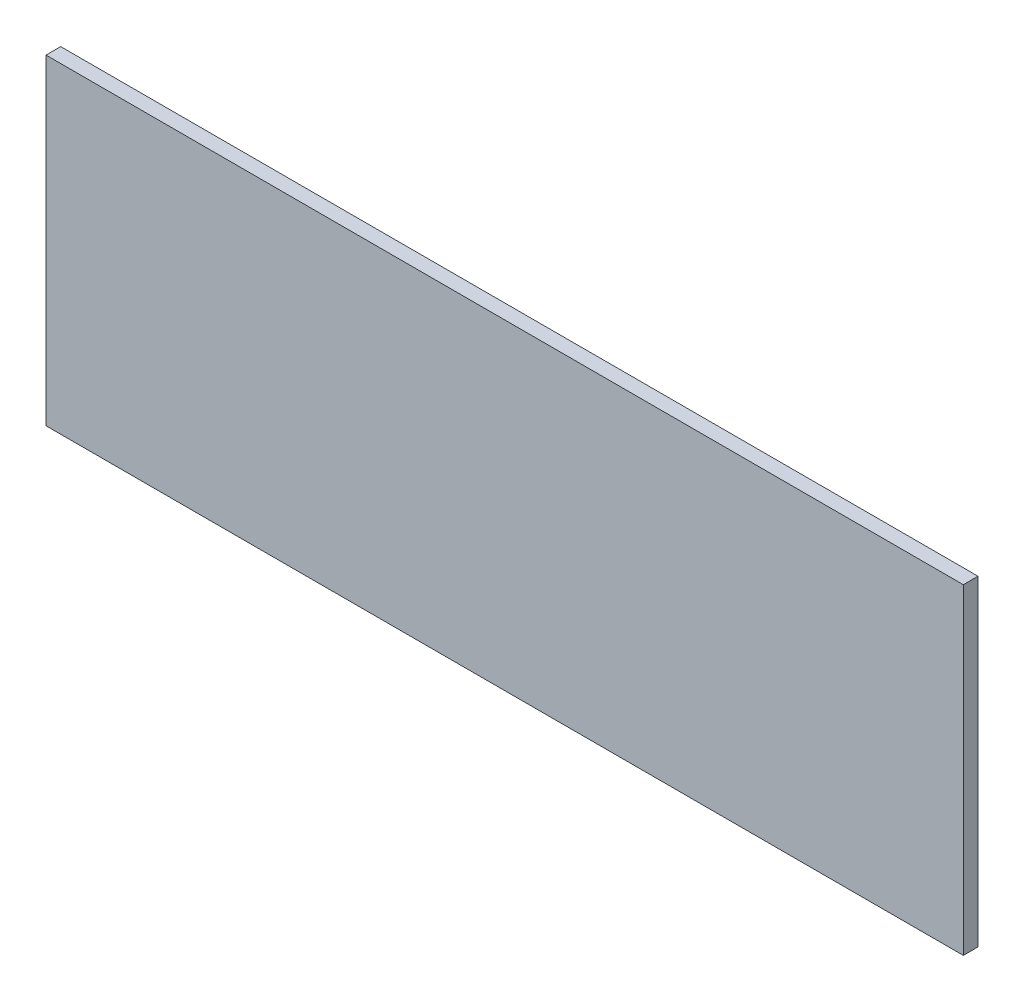
SolidWorks part; units mm, degrees
ref_plane "前视基准面" through (0, 0, 0) normal (0, 0, 1) x (1, 0, 0)
ref_plane "上视基准面" through (0, 0, 0) normal (0, 1, 0) x (1, 0, 0)
ref_plane "右视基准面" through (0, 0, 0) normal (1, 0, 0) x (0, 0, -1)
sketch "草图1" plane through (0, 0, 0) normal (0, 0, 1) x (1, 0, 0)
  line L1 (-46.8719, 3.2048) -> (3.1281, 3.2048)
  line L2 (-46.8719, 3.2048) -> (-46.8719, -14.2952)
  line L3 (-46.8719, -14.2952) -> (3.1281, -14.2952)
  line L4 (3.1281, 3.2048) -> (3.1281, -14.2952)
  dimension "D1" = 17.5
  dimension "D2" = 50
extrude "凸台-拉伸1" add sketch "草图1" along normal blind 0.8
